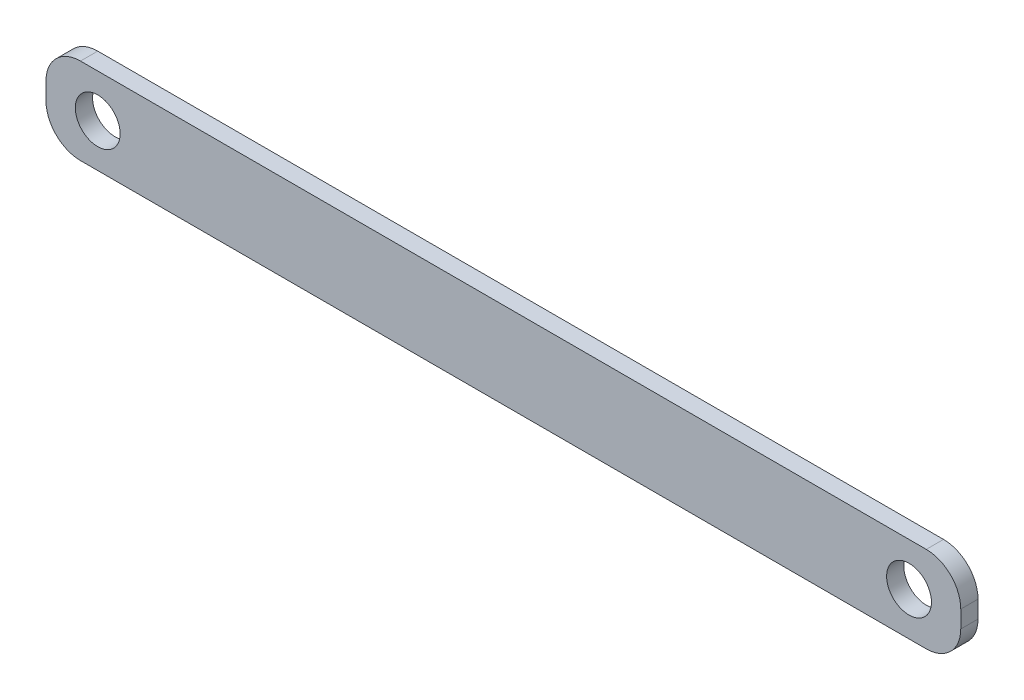
SolidWorks part; units mm, degrees
ref_plane "Front Plane" through (0, 0, 0) normal (0, 0, 1) x (1, 0, 0)
ref_plane "Top Plane" through (0, 0, 0) normal (0, 1, 0) x (1, 0, 0)
ref_plane "Right Plane" through (0, 0, 0) normal (1, 0, 0) x (0, 0, -1)
sketch "Sketch1" plane through (0, 0, 0) normal (0, 0, 1) x (1, 0, 0)
  line L0 (0, 71.4387) -> (0, -31.1886) construction
  line L1 (-125.229, 12.5) -> (120, 12.5)
  line L2 (-135.229, 2.5) -> (-135.229, -2.5)
  line L3 (-125.229, -12.5) -> (120, -12.5)
  line L4 (130, 2.5) -> (130, -2.5)
  line L7 (-115, 0) -> (115, 0) construction
  line L8 (-120.229, -20.9054) -> (-120.229, 3.557) construction
  circle A0 centre (-120.229, 0) radius 6.5
  circle A1 centre (115, 0) radius 6.5
  arc A2 (120, -12.5) -> (130, -2.5) centre (120, -2.5) ccw
  arc A3 (120, 12.5) -> (130, 2.5) centre (120, 2.5) cw
  arc A4 (-135.229, -2.5) -> (-125.229, -12.5) centre (-125.229, -2.5) ccw
  arc A5 (-125.229, 12.5) -> (-135.229, 2.5) centre (-125.229, 2.5) ccw
  point P0 (0, 0)
  dimension "D4" = 13
  dimension "D5" = 10
  dimension "D1" = 15
  dimension "D2" = 230
  dimension "D3" = 15
  dimension "D6" = 120.229
extrude "Boss-Extrude1" add sketch "Sketch1" along normal mid plane 5
